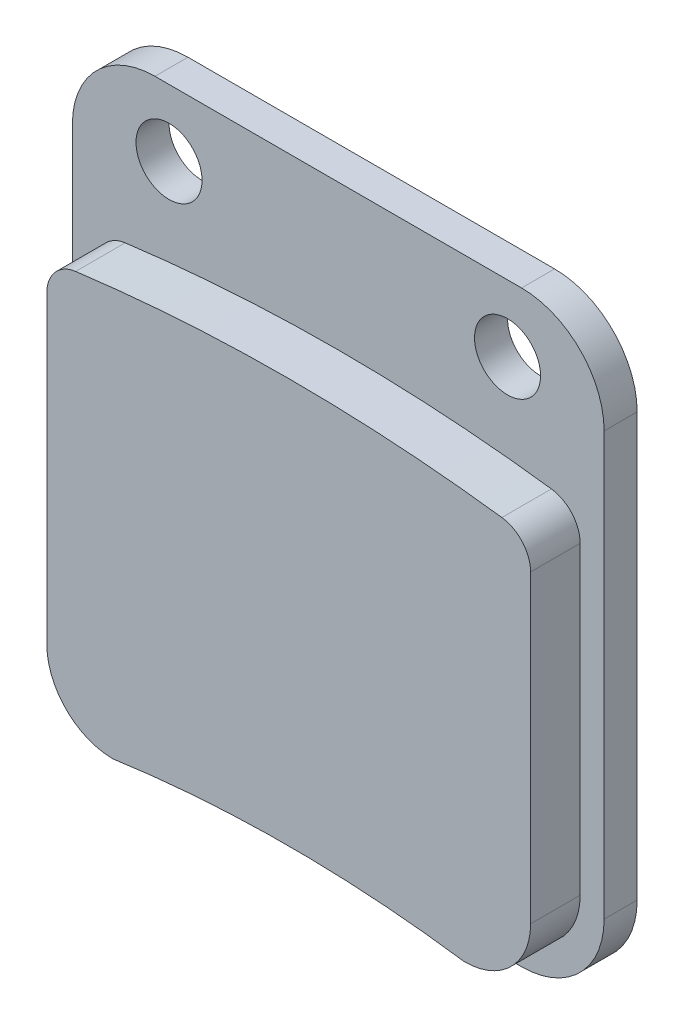
SolidWorks part; units mm, degrees
material "Plain Carbon Steel"
ref_plane "Front Plane" through (0, 0, 0) normal (0, 0, 1) x (1, 0, 0)
ref_plane "Top Plane" through (0, 0, 0) normal (0, 1, 0) x (1, 0, 0)
ref_plane "Right Plane" through (0, 0, 0) normal (1, 0, 0) x (0, 0, -1)
sketch "Sketch1" plane through (0, 0, 0) normal (0, 0, 1) x (1, 0, 0)
  line L0 (0, 0) -> (0, 17.4818) construction
  line L1 (-14.097, -22.606) -> (14.097, -22.606)
  line L2 (-20.447, -16.256) -> (-20.447, 16.256)
  line L3 (-14.097, 22.606) -> (14.097, 22.606)
  line L4 (20.447, -16.256) -> (20.447, 16.256)
  line L5 (-20.447, -22.606) -> (20.447, 22.606) construction
  line L6 (-20.447, 22.606) -> (20.447, -22.606) construction
  line L7 (-13.0175, 17.4818) -> (13.0175, 17.4818) construction
  line L8 (0, 0) -> (0, -5.5789) construction
  circle A0 centre (0, -5.5789) radius 15.875 construction
  circle A1 centre (13.0175, 17.4818) radius 2.54
  circle A2 centre (-13.0175, 17.4818) radius 2.54
  arc A3 (-14.097, -22.606) -> (-20.447, -16.256) centre (-14.097, -16.256) cw
  arc A4 (14.097, -22.606) -> (20.447, -16.256) centre (14.097, -16.256) ccw
  arc A5 (14.097, 22.606) -> (20.447, 16.256) centre (14.097, 16.256) cw
  arc A6 (-20.447, 16.256) -> (-14.097, 22.606) centre (-14.097, 16.256) cw
  point P0 (0, 0)
  dimension "D3" = 31.75
  dimension "D5" = 5.08
  dimension "D6" = 6.35
  dimension "D1" = 45.212
  dimension "D2" = 40.894
  dimension "D4" = 26.035
extrude "Boss-Extrude1" add sketch "Sketch1" along normal blind 2.54
sketch "Sketch2" plane through (0, 0, 2.54) normal (0, 0, 1) x (1, 0, 0)
  line L0 (0, 0) -> (0, -115.57) construction
  line L3 (-18.6033, -15.5838) -> (-18.6033, 7.849)
  line L4 (18.6033, -15.5838) -> (18.6033, 7.849)
  arc A0 (16.3911, 10.3678) -> (-16.3911, 10.3678) centre (0, -115.57) ccw
  arc A1 (13.4724, -20.6566) -> (-13.5233, -20.6638) centre (0, -115.57) ccw
  arc A4 (-18.6033, -15.5838) -> (-13.5233, -20.6638) centre (-13.5233, -15.5838) ccw
  arc A5 (13.4724, -20.6566) -> (18.6033, -15.5838) centre (13.5233, -15.5768) ccw
  arc A6 (18.6033, 7.849) -> (16.3911, 10.3678) centre (16.0633, 7.849) ccw
  arc A7 (-18.6033, 7.849) -> (-16.3911, 10.3678) centre (-16.0633, 7.849) cw
  dimension "D2" = 254
  dimension "D3" = 2.54
  dimension "D1" = 115.57
extrude "Boss-Extrude2" add sketch "Sketch2" along normal blind 3.81
